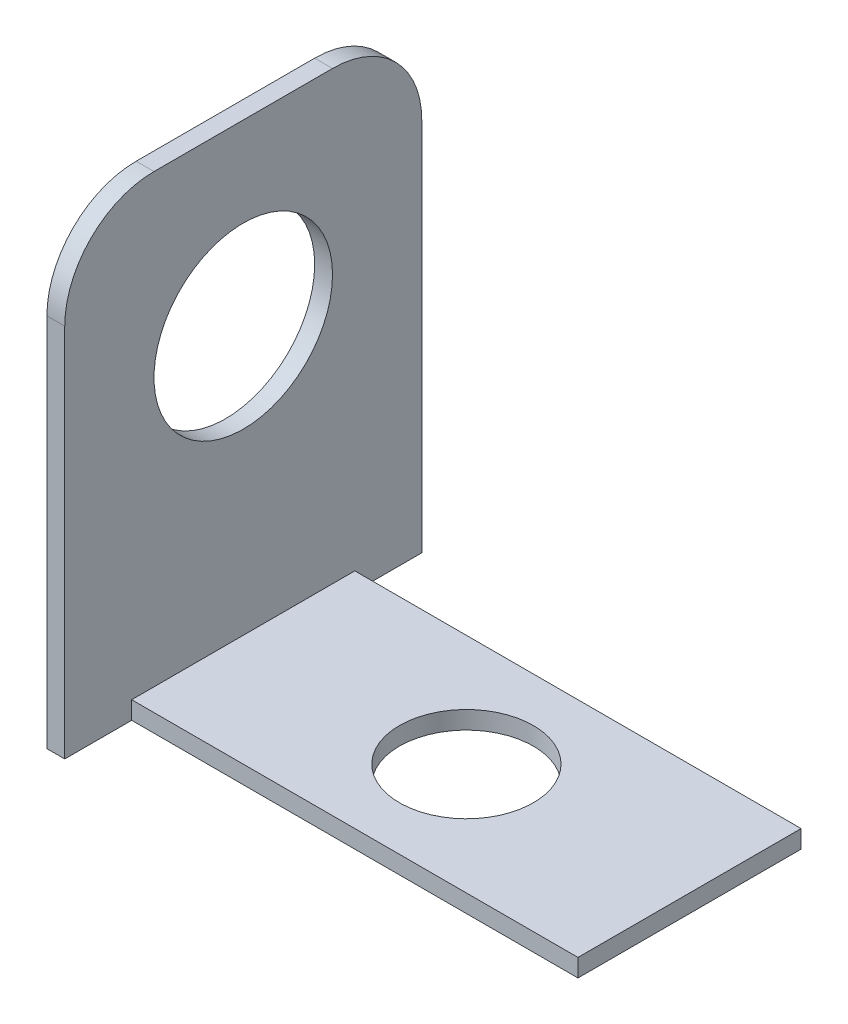
SolidWorks part; units mm, degrees
ref_plane "Plano frontal" through (0, 0, 0) normal (0, 0, 1) x (1, 0, 0)
ref_plane "Plano superior" through (0, 0, 0) normal (0, 1, 0) x (1, 0, 0)
ref_plane "Plano direito" through (0, 0, 0) normal (1, 0, 0) x (0, 0, -1)
sketch "Esboço1" plane through (0, 0, 0) normal (0, 0, 1) x (1, 0, 0)
  line L0 (0, 0) -> (0, 50)
  line L1 (0, 50) -> (-2, 50)
  line L2 (-2, 50) -> (-2, -2)
  line L3 (-2, -2) -> (50, -2)
  line L4 (50, -2) -> (50, 0)
  line L5 (50, 0) -> (0, 0)
  dimension "D1" = 50
  dimension "D2" = 2
  dimension "D3" = 52
  dimension "D4" = 52
  dimension "D5" = 2
extrude "Ressalto-extrusão1" add sketch "Esboço1" along normal blind 40 contours L0 L1 L2 L3 L4 L5
sketch "Esboço2" plane through (0, 0, 0) normal (1, 0, 0) x (0, 0, -1)
  line L0 (-20, 50) -> (-20, 30)
  line L1 (-40, 50) -> (0, 50) construction
  circle A0 centre (-20, 30) radius 10
  dimension "D2" = 20
  dimension "D1" = 20
extrude "Corte-extrusão1" cut sketch "Esboço2" against normal blind 40
sketch "Esboço3" plane through (0, 0, 0) normal (0, 1, 0) x (1, 0, 0)
  line L0 (50, -20) -> (25, -20)
  line L1 (50, -40) -> (50, 0) construction
  circle A0 centre (25, -20) radius 7.5
  dimension "D2" = 15
  dimension "D1" = 25
extrude "Corte-extrusão2" cut sketch "Esboço3" against normal blind 40
fillet "Filete1" radius 10 2 edges at (-1, 50, 0) (-1, 50, 40)
sketch "Esboço4" plane through (0, 0, 0) normal (0, 1, 0) x (1, 0, 0)
  line L0 (50, -20) -> (50, -32.5)
  line L1 (50, -40) -> (50, 0) construction
  line L2 (50, -32.5) -> (0, -32.5)
  line L3 (0, -40) -> (0, 0) construction
  line L4 (0, -32.5) -> (0, -40)
  line L5 (0, -40) -> (50, -40)
  line L6 (50, -40) -> (50, -20)
  line L7 (50, -20) -> (50, -7.5)
  line L8 (50, -7.5) -> (0, -7.5)
  line L9 (0, -7.5) -> (0, 0)
  line L10 (0, 0) -> (50, 0)
  line L11 (50, 0) -> (50, -7.5)
  line M2 (50, 0) -> (0, 0)
  line M3 (0, 0) -> (0, -40)
  line M4 (0, -40) -> (50, -40)
  line M5 (50, -40) -> (50, 0)
  dimension "D1" = 12.5
  dimension "D2" = 12.5
extrude "Corte-extrusão3" cut sketch "Esboço4" against normal blind 290 contours L2 M5 M3 M4 | L8 M5 M2 M3
